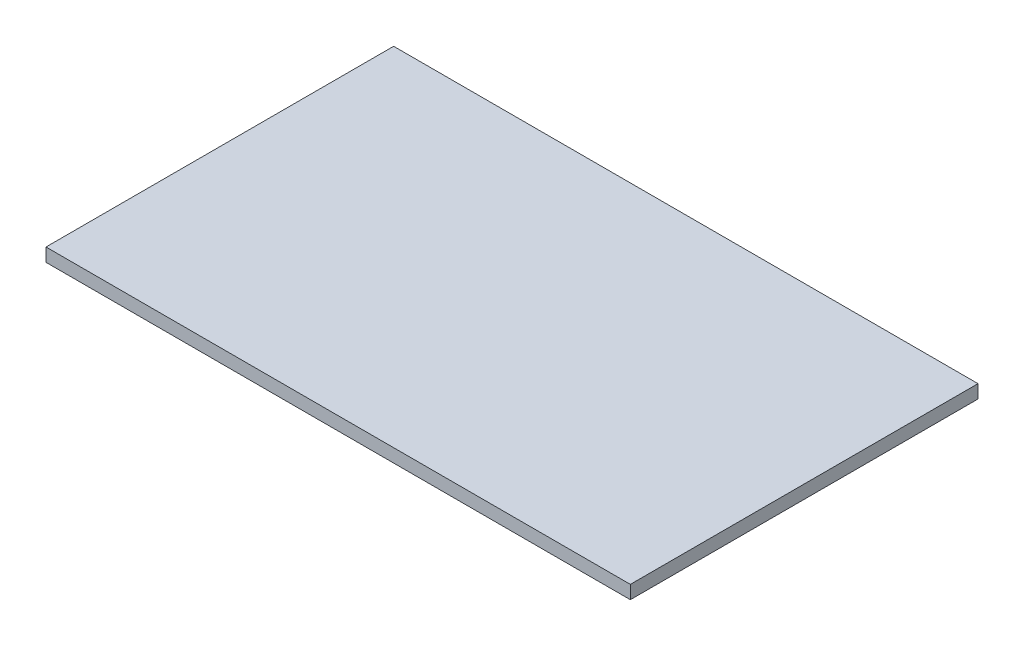
SolidWorks part; units mm, degrees
ref_plane "Front Plane" through (0, 0, 0) normal (0, 0, 1) x (1, 0, 0)
ref_plane "Top Plane" through (0, 0, 0) normal (0, 1, 0) x (1, 0, 0)
ref_plane "Right Plane" through (0, 0, 0) normal (1, 0, 0) x (0, 0, -1)
sketch "Sketch1" plane through (0, 0, 0) normal (0, 1, 0) x (1, 0, 0)
  line L1 (-395, -235) -> (395, -235)
  line L2 (-395, -235) -> (-395, 235)
  line L3 (-395, 235) -> (395, 235)
  line L4 (395, -235) -> (395, 235)
  line L5 (-395, -235) -> (395, 235) construction
  line L6 (-395, 235) -> (395, -235) construction
  point P0 (0, 0)
  dimension "D1" = 790
  dimension "D2" = 470
extrude "Boss-Extrude1" add sketch "Sketch1" along normal blind 18
equation "\"Case_Width\" = 790mm"
equation "\"Case_Depth\" = 470mm"
equation "\"D1@Sketch1\"=\"Case_Width\""
equation "\"D2@Sketch1\"=\"Case_Depth\""
equation "\"Tank_Width\" = 660mm"
equation "\"WoodSheet_Thickness\" = 18mm"
equation "\"D1@Boss-Extrude1\"=\"WoodSheet_Thickness\""
